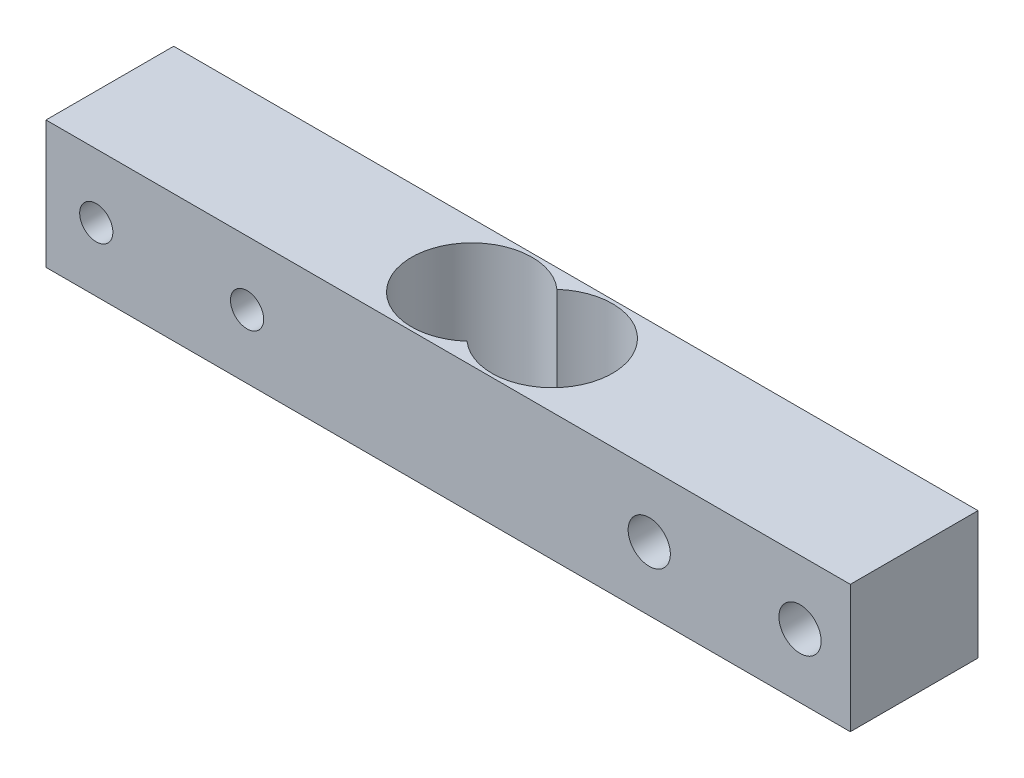
SolidWorks part; units mm, degrees
ref_plane "Płaszczyzna przednia" through (0, 0, 0) normal (0, 0, 1) x (1, 0, 0)
ref_plane "Płaszczyzna górna" through (0, 0, 0) normal (0, 1, 0) x (1, 0, 0)
ref_plane "Płaszczyzna prawa" through (0, 0, 0) normal (1, 0, 0) x (0, 0, -1)
sketch "Sketch1" plane through (0, 0, 0) normal (0, 0, 1) x (1, 0, 0)
  line L0 (-4, 0) -> (4, 0) construction
  line L1 (-40, -6.35) -> (40, -6.35)
  line L2 (-40, -6.35) -> (-40, 6.35)
  line L3 (-40, 6.35) -> (40, 6.35)
  line L4 (40, -6.35) -> (40, 6.35)
  line L5 (-40, -6.35) -> (40, 6.35) construction
  line L6 (-40, 6.35) -> (40, -6.35) construction
  circle A0 centre (-4, 0) radius 6
  circle A1 centre (4, 0) radius 6
  point P0 (0, 0)
  point P10 (0, 0)
  dimension "D3" = 12
  dimension "D1" = 12.7
  dimension "D2" = 80
  dimension "D4" = 8
extrude "Boss-Extrude1" add sketch "Sketch1" against normal blind 12.7 contours L3 L4 L1 L2
hole_wizard "Tap Drill for M5 Tap1" positions "Sketch2" profile "Sketch3" hole size "M5" standard "ISO" end condition through all
sketch "Sketch2" plane through (0, 0, 0) normal (0, 0, 1) x (1, 0, 0)
  line L1 (40, -6.35) -> (40, 6.35) construction
  point P0 (20, 0)
  point P2 (35, 0)
  dimension "D1" = 5
  dimension "D2" = 15
sketch "Sketch3" plane through (20, 0, 0) normal (1, 0, 0) x (0, -1, 0)
  line L0 (0, 0) -> (0, 12.7)
  line L1 (0, 12.7) -> (2.1, 12.7)
  line L2 (2.1, 12.7) -> (2.1, 0)
  line L5 (2.1, 0) -> (0, 0)
  line L11 (0, -6.35) -> (0, 107.95) construction
  dimension "Thru Hole Dia." = 4.2
  dimension "Thru Hole Depth" = 12.7
hole_wizard "Tap Drill for M4 Tap1" positions "Sketch4" profile "Sketch5" hole size "M4" standard "ISO" end condition through all
sketch "Sketch4" plane through (0, 0, 0) normal (0, 0, 1) x (1, 0, 0)
  line L1 (-40, -6.35) -> (-40, 6.35) construction
  point P0 (-35, 0)
  point P2 (-20, 0)
  dimension "D1" = 5
  dimension "D2" = 15
sketch "Sketch5" plane through (-35, 0, 0) normal (1, 0, 0) x (0, -1, 0)
  line L0 (0, 0) -> (0, 12.7)
  line L1 (0, 12.7) -> (1.65, 12.7)
  line L2 (1.65, 12.7) -> (1.65, 0)
  line L5 (1.65, 0) -> (0, 0)
  line L11 (0, -6.35) -> (0, 107.95) construction
  dimension "Thru Hole Dia." = 3.3
  dimension "Thru Hole Depth" = 12.7
sketch "Sketch6" plane through (0, 6.35, 0) normal (0, 1, 0) x (1, 0, 0)
  circle A0 centre (-4, 6.35) radius 6
  circle A1 centre (4, 6.35) radius 6
  dimension "D2" = 12
  dimension "D1" = 6.35
extrude "Cut-Extrude1" cut sketch "Sketch6" against normal through all contours A0 | A1
equation "\"D1@Sketch6\"=\"D1@Boss-Extrude1\"/2"
